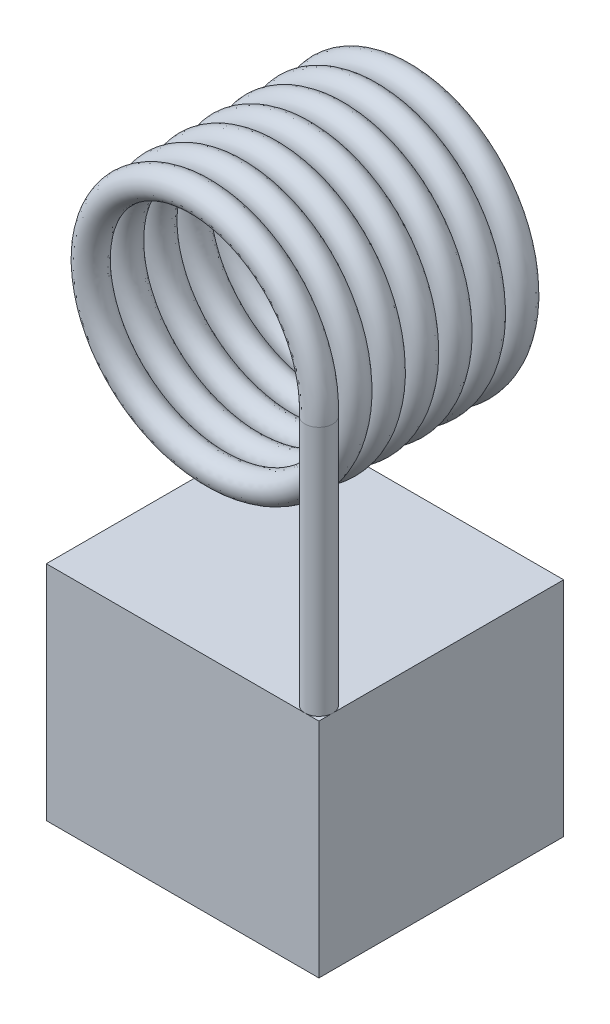
SolidWorks part; units mm, degrees
ref_plane "Front Plane" through (0, 0, 0) normal (0, 0, 1) x (1, 0, 0)
ref_plane "Top Plane" through (0, 0, 0) normal (0, 1, 0) x (1, 0, 0)
ref_plane "Right Plane" through (0, 0, 0) normal (1, 0, 0) x (0, 0, -1)
sketch "Sketch1" plane through (0, 0, 0) normal (0, 0, 1) x (1, 0, 0)
  line L5 (38.5919, -38.5919) -> (-39.5131, 39.5131) construction
  line L6 (38.5864, 38.5864) -> (-38.5864, -38.5864) construction
  circle A0 centre (0, 0) radius 55.88
  point P0 (0, 0)
  dimension "D3" = 111.76
curve "Helix/Spiral1" pitch 15.24 height 99.06 turns 6.5
sketch "Sketch2" plane through (0, 0, 0) normal (0, 1, 0) x (1, 0, 0)
  circle A0 centre (-55.88, 0) radius 6.35
  spline S0 degree 3 poles (-55.88, 0) (-55.88, -0.1534) (-55.2059, -0.4609) (-52.2086, -0.9215) (-47.3331, -1.3822) (-40.7549, -1.843) (-32.7104, -2.3037) (-23.4892, -2.7645) (-13.4229, -3.2252) (-2.8738, -3.686) (7.7787, -4.1467) (18.1514, -4.6074) (27.8711, -5.0682) (36.5881, -5.5289) (43.9888, -5.9897) (49.8071, -6.4504) (53.8335, -6.9112) (55.9233, -7.3719) (56.0012, -7.8327) (54.0644, -8.2934) (50.1827, -8.7541) (44.4956, -9.2149) (37.2078, -9.6756) (28.5815, -10.1364) (18.9269, -10.5971) (8.5914, -11.0579) (-2.0532, -11.5186) (-12.6239, -11.9793) (-22.7404, -12.4401) (-32.0389, -12.9008) (-40.1847, -13.3616) (-46.8849, -13.8223) (-51.8984, -14.2831) (-55.0449, -14.7438) (-56.2111, -15.2046) (-55.3551, -15.6653) (-52.5076, -16.126) (-47.7713, -16.5868) (-41.3163, -17.0475) (-33.375, -17.5083) (-24.233, -17.969) (-14.2192, -18.4298) (-3.6938, -18.8905) (6.9644, -19.3513) (17.372, -19.812) (27.1547, -20.2727) (35.9605, -20.7335) (43.4727, -21.1942) (49.4208, -21.655) (53.5911, -22.1157) (55.8334, -22.5765) (56.0671, -23.0372) (54.2838, -23.498) (50.5476, -23.9587) (44.9929, -24.4194) (37.8196, -24.8802) (29.2857, -25.3409) (19.6983, -25.8017) (9.4022, -26.2624) (-1.2321, -26.7232) (-11.8221, -27.1839) (-21.9868, -27.6447) (-31.3605, -28.1054) (-39.606, -28.5661) (-46.4267, -29.0269) (-51.5772, -29.4876) (-54.8721, -29.9484) (-56.1931, -30.4091) (-55.4924, -30.8699) (-52.7955, -31.3306) (-48.1992, -31.7913) (-41.8689, -32.2521) (-34.0324, -32.7128) (-24.9716, -33.1736) (-15.0124, -33.6343) (-4.5131, -34.0951) (6.1485, -34.5558) (16.589, -35.0166) (26.4326, -35.4773) (35.3253, -35.938) (42.9472, -36.3988) (49.0241, -36.8595) (53.3373, -37.3203) (55.7316, -37.781) (56.1211, -38.2418) (54.4915, -38.7025) (50.9016, -39.1633) (45.4806, -39.624) (38.4233, -40.0847) (29.9838, -40.5455) (20.4656, -41.0062) (10.2111, -41.467) (-0.4107, -41.9277) (-11.0178, -42.3885) (-21.2284, -42.8492) (-30.6754, -43.31) (-39.0188, -43.7707) (-45.9585, -44.2314) (-51.2449, -44.6922) (-54.6877, -45.1529) (-56.1631, -45.6137) (-55.618, -46.0744) (-53.072, -46.5352) (-48.6168, -46.9959) (-42.4126, -47.4567) (-34.6826, -47.9174) (-25.7048, -48.3781) (-15.8023, -48.8389) (-5.3314, -49.2996) (5.3314, -49.7604) (15.8023, -50.2211) (25.7048, -50.6819) (34.6826, -51.1426) (42.4126, -51.6033) (48.6168, -52.0641) (53.072, -52.5248) (55.618, -52.9856) (56.1631, -53.4463) (54.6877, -53.9071) (51.2449, -54.3678) (45.9585, -54.8286) (39.0188, -55.2893) (30.6754, -55.75) (21.2284, -56.2108) (11.0178, -56.6715) (0.4107, -57.1323) (-10.2111, -57.593) (-20.4656, -58.0538) (-29.9838, -58.5145) (-38.4233, -58.9753) (-45.4806, -59.436) (-50.9016, -59.8967) (-54.4915, -60.3575) (-56.1211, -60.8182) (-55.7316, -61.279) (-53.3373, -61.7397) (-49.0241, -62.2005) (-42.9472, -62.6612) (-35.3253, -63.122) (-26.4326, -63.5827) (-16.589, -64.0434) (-6.1485, -64.5042) (4.5131, -64.9649) (15.0124, -65.4257) (24.9716, -65.8864) (34.0324, -66.3472) (41.8689, -66.8079) (48.1992, -67.2687) (52.7955, -67.7294) (55.4924, -68.1901) (56.1931, -68.6509) (54.8721, -69.1116) (51.5772, -69.5724) (46.4267, -70.0331) (39.606, -70.4939) (31.3605, -70.9546) (21.9868, -71.4153) (11.8221, -71.8761) (1.2321, -72.3368) (-9.4022, -72.7976) (-19.6983, -73.2583) (-29.2857, -73.7191) (-37.8196, -74.1798) (-44.9929, -74.6406) (-50.5476, -75.1013) (-54.2838, -75.562) (-56.0671, -76.0228) (-55.8334, -76.4835) (-53.5911, -76.9443) (-49.4208, -77.405) (-43.4727, -77.8658) (-35.9605, -78.3265) (-27.1547, -78.7873) (-17.372, -79.248) (-6.9644, -79.7087) (3.6938, -80.1695) (14.2192, -80.6302) (24.233, -81.091) (33.375, -81.5517) (41.3163, -82.0125) (47.7713, -82.4732) (52.5076, -82.934) (55.3551, -83.3947) (56.2111, -83.8554) (55.0449, -84.3162) (51.8984, -84.7769) (46.8849, -85.2377) (40.1847, -85.6984) (32.0389, -86.1592) (22.7404, -86.6199) (12.6239, -87.0807) (2.0532, -87.5414) (-8.5914, -88.0021) (-18.9269, -88.4629) (-28.5815, -88.9236) (-37.2078, -89.3844) (-44.4956, -89.8451) (-50.1827, -90.3059) (-54.0644, -90.7666) (-56.0012, -91.2273) (-55.9233, -91.6881) (-53.8335, -92.1488) (-49.8071, -92.6096) (-43.9888, -93.0703) (-36.5881, -93.5311) (-27.8711, -93.9918) (-18.1514, -94.4526) (-7.7787, -94.9133) (2.8738, -95.374) (13.4229, -95.8348) (23.4892, -96.2955) (32.7104, -96.7563) (40.7549, -97.217) (47.3331, -97.6778) (52.2086, -98.1385) (55.2059, -98.5991) (55.88, -98.9066) (55.88, -99.06) knots 0 0 0 0 0.004651 0.009302 0.013953 0.018605 0.023256 0.027907 0.032558 0.037209 0.04186 0.046512 0.051163 0.055814 0.060465 0.065116 0.069767 0.074419 0.07907 0.083721 0.088372 0.093023 0.097674 0.102326 0.106977 0.111628 0.116279 0.12093 0.125581 0.130233 0.134884 0.139535 0.144186 0.148837 0.153488 0.15814 0.162791 0.167442 0.172093 0.176744 0.181395 0.186047 0.190698 0.195349 0.2 0.204651 0.209302 0.213953 0.218605 0.223256 0.227907 0.232558 0.237209 0.24186 0.246512 0.251163 0.255814 0.260465 0.265116 0.269767 0.274419 0.27907 0.283721 0.288372 0.293023 0.297674 0.302326 0.306977 0.311628 0.316279 0.32093 0.325581 0.330233 0.334884 0.339535 0.344186 0.348837 0.353488 0.35814 0.362791 0.367442 0.372093 0.376744 0.381395 0.386047 0.390698 0.395349 0.4 0.404651 0.409302 0.413953 0.418605 0.423256 0.427907 0.432558 0.437209 0.44186 0.446512 0.451163 0.455814 0.460465 0.465116 0.469767 0.474419 0.47907 0.483721 0.488372 0.493023 0.497674 0.502326 0.506977 0.511628 0.516279 0.52093 0.525581 0.530233 0.534884 0.539535 0.544186 0.548837 0.553488 0.55814 0.562791 0.567442 0.572093 0.576744 0.581395 0.586047 0.590698 0.595349 0.6 0.604651 0.609302 0.613953 0.618605 0.623256 0.627907 0.632558 0.637209 0.64186 0.646512 0.651163 0.655814 0.660465 0.665116 0.669767 0.674419 0.67907 0.683721 0.688372 0.693023 0.697674 0.702326 0.706977 0.711628 0.716279 0.72093 0.725581 0.730233 0.734884 0.739535 0.744186 0.748837 0.753488 0.75814 0.762791 0.767442 0.772093 0.776744 0.781395 0.786047 0.790698 0.795349 0.8 0.804651 0.809302 0.813953 0.818605 0.823256 0.827907 0.832558 0.837209 0.84186 0.846512 0.851163 0.855814 0.860465 0.865116 0.869767 0.874419 0.87907 0.883721 0.888372 0.893023 0.897674 0.902326 0.906977 0.911628 0.916279 0.92093 0.925581 0.930233 0.934884 0.939535 0.944186 0.948837 0.953488 0.95814 0.962791 0.967442 0.972093 0.976744 0.981395 0.986047 0.990698 0.995349 1 1 1 1 construction
  dimension "D1" = 12.7
sweep "Sweep1" add profiles "Sketch2" path "Helix/Spiral1"
sketch "Sketch3" plane through (0, 0, 0) normal (0, -1, 0) x (1, 0, 0)
  circle A0 centre (55.88, 99.06) radius 6.35
  circle A1 centre (-55.88, 0) radius 6.35
  spline S0 degree 3 poles (-55.88, 0) (-55.88, 0.1534) (-55.2059, 0.4609) (-52.2086, 0.9215) (-47.3331, 1.3822) (-40.7549, 1.843) (-32.7104, 2.3037) (-23.4892, 2.7645) (-13.4229, 3.2252) (-2.8738, 3.686) (7.7787, 4.1467) (18.1514, 4.6074) (27.8711, 5.0682) (36.5881, 5.5289) (43.9888, 5.9897) (49.8071, 6.4504) (53.8335, 6.9112) (55.9233, 7.3719) (56.0012, 7.8327) (54.0644, 8.2934) (50.1827, 8.7541) (44.4956, 9.2149) (37.2078, 9.6756) (28.5815, 10.1364) (18.9269, 10.5971) (8.5914, 11.0579) (-2.0532, 11.5186) (-12.6239, 11.9793) (-22.7404, 12.4401) (-32.0389, 12.9008) (-40.1847, 13.3616) (-46.8849, 13.8223) (-51.8984, 14.2831) (-55.0449, 14.7438) (-56.2111, 15.2046) (-55.3551, 15.6653) (-52.5076, 16.126) (-47.7713, 16.5868) (-41.3163, 17.0475) (-33.375, 17.5083) (-24.233, 17.969) (-14.2192, 18.4298) (-3.6938, 18.8905) (6.9644, 19.3513) (17.372, 19.812) (27.1547, 20.2727) (35.9605, 20.7335) (43.4727, 21.1942) (49.4208, 21.655) (53.5911, 22.1157) (55.8334, 22.5765) (56.0671, 23.0372) (54.2838, 23.498) (50.5476, 23.9587) (44.9929, 24.4194) (37.8196, 24.8802) (29.2857, 25.3409) (19.6983, 25.8017) (9.4022, 26.2624) (-1.2321, 26.7232) (-11.8221, 27.1839) (-21.9868, 27.6447) (-31.3605, 28.1054) (-39.606, 28.5661) (-46.4267, 29.0269) (-51.5772, 29.4876) (-54.8721, 29.9484) (-56.1931, 30.4091) (-55.4924, 30.8699) (-52.7955, 31.3306) (-48.1992, 31.7913) (-41.8689, 32.2521) (-34.0324, 32.7128) (-24.9716, 33.1736) (-15.0124, 33.6343) (-4.5131, 34.0951) (6.1485, 34.5558) (16.589, 35.0166) (26.4326, 35.4773) (35.3253, 35.938) (42.9472, 36.3988) (49.0241, 36.8595) (53.3373, 37.3203) (55.7316, 37.781) (56.1211, 38.2418) (54.4915, 38.7025) (50.9016, 39.1633) (45.4806, 39.624) (38.4233, 40.0847) (29.9838, 40.5455) (20.4656, 41.0062) (10.2111, 41.467) (-0.4107, 41.9277) (-11.0178, 42.3885) (-21.2284, 42.8492) (-30.6754, 43.31) (-39.0188, 43.7707) (-45.9585, 44.2314) (-51.2449, 44.6922) (-54.6877, 45.1529) (-56.1631, 45.6137) (-55.618, 46.0744) (-53.072, 46.5352) (-48.6168, 46.9959) (-42.4126, 47.4567) (-34.6826, 47.9174) (-25.7048, 48.3781) (-15.8023, 48.8389) (-5.3314, 49.2996) (5.3314, 49.7604) (15.8023, 50.2211) (25.7048, 50.6819) (34.6826, 51.1426) (42.4126, 51.6033) (48.6168, 52.0641) (53.072, 52.5248) (55.618, 52.9856) (56.1631, 53.4463) (54.6877, 53.9071) (51.2449, 54.3678) (45.9585, 54.8286) (39.0188, 55.2893) (30.6754, 55.75) (21.2284, 56.2108) (11.0178, 56.6715) (0.4107, 57.1323) (-10.2111, 57.593) (-20.4656, 58.0538) (-29.9838, 58.5145) (-38.4233, 58.9753) (-45.4806, 59.436) (-50.9016, 59.8967) (-54.4915, 60.3575) (-56.1211, 60.8182) (-55.7316, 61.279) (-53.3373, 61.7397) (-49.0241, 62.2005) (-42.9472, 62.6612) (-35.3253, 63.122) (-26.4326, 63.5827) (-16.589, 64.0434) (-6.1485, 64.5042) (4.5131, 64.9649) (15.0124, 65.4257) (24.9716, 65.8864) (34.0324, 66.3472) (41.8689, 66.8079) (48.1992, 67.2687) (52.7955, 67.7294) (55.4924, 68.1901) (56.1931, 68.6509) (54.8721, 69.1116) (51.5772, 69.5724) (46.4267, 70.0331) (39.606, 70.4939) (31.3605, 70.9546) (21.9868, 71.4153) (11.8221, 71.8761) (1.2321, 72.3368) (-9.4022, 72.7976) (-19.6983, 73.2583) (-29.2857, 73.7191) (-37.8196, 74.1798) (-44.9929, 74.6406) (-50.5476, 75.1013) (-54.2838, 75.562) (-56.0671, 76.0228) (-55.8334, 76.4835) (-53.5911, 76.9443) (-49.4208, 77.405) (-43.4727, 77.8658) (-35.9605, 78.3265) (-27.1547, 78.7873) (-17.372, 79.248) (-6.9644, 79.7087) (3.6938, 80.1695) (14.2192, 80.6302) (24.233, 81.091) (33.375, 81.5517) (41.3163, 82.0125) (47.7713, 82.4732) (52.5076, 82.934) (55.3551, 83.3947) (56.2111, 83.8554) (55.0449, 84.3162) (51.8984, 84.7769) (46.8849, 85.2377) (40.1847, 85.6984) (32.0389, 86.1592) (22.7404, 86.6199) (12.6239, 87.0807) (2.0532, 87.5414) (-8.5914, 88.0021) (-18.9269, 88.4629) (-28.5815, 88.9236) (-37.2078, 89.3844) (-44.4956, 89.8451) (-50.1827, 90.3059) (-54.0644, 90.7666) (-56.0012, 91.2273) (-55.9233, 91.6881) (-53.8335, 92.1488) (-49.8071, 92.6096) (-43.9888, 93.0703) (-36.5881, 93.5311) (-27.8711, 93.9918) (-18.1514, 94.4526) (-7.7787, 94.9133) (2.8738, 95.374) (13.4229, 95.8348) (23.4892, 96.2955) (32.7104, 96.7563) (40.7549, 97.217) (47.3331, 97.6778) (52.2086, 98.1385) (55.2059, 98.5991) (55.88, 98.9066) (55.88, 99.06) knots 0 0 0 0 0.004651 0.009302 0.013953 0.018605 0.023256 0.027907 0.032558 0.037209 0.04186 0.046512 0.051163 0.055814 0.060465 0.065116 0.069767 0.074419 0.07907 0.083721 0.088372 0.093023 0.097674 0.102326 0.106977 0.111628 0.116279 0.12093 0.125581 0.130233 0.134884 0.139535 0.144186 0.148837 0.153488 0.15814 0.162791 0.167442 0.172093 0.176744 0.181395 0.186047 0.190698 0.195349 0.2 0.204651 0.209302 0.213953 0.218605 0.223256 0.227907 0.232558 0.237209 0.24186 0.246512 0.251163 0.255814 0.260465 0.265116 0.269767 0.274419 0.27907 0.283721 0.288372 0.293023 0.297674 0.302326 0.306977 0.311628 0.316279 0.32093 0.325581 0.330233 0.334884 0.339535 0.344186 0.348837 0.353488 0.35814 0.362791 0.367442 0.372093 0.376744 0.381395 0.386047 0.390698 0.395349 0.4 0.404651 0.409302 0.413953 0.418605 0.423256 0.427907 0.432558 0.437209 0.44186 0.446512 0.451163 0.455814 0.460465 0.465116 0.469767 0.474419 0.47907 0.483721 0.488372 0.493023 0.497674 0.502326 0.506977 0.511628 0.516279 0.52093 0.525581 0.530233 0.534884 0.539535 0.544186 0.548837 0.553488 0.55814 0.562791 0.567442 0.572093 0.576744 0.581395 0.586047 0.590698 0.595349 0.6 0.604651 0.609302 0.613953 0.618605 0.623256 0.627907 0.632558 0.637209 0.64186 0.646512 0.651163 0.655814 0.660465 0.665116 0.669767 0.674419 0.67907 0.683721 0.688372 0.693023 0.697674 0.702326 0.706977 0.711628 0.716279 0.72093 0.725581 0.730233 0.734884 0.739535 0.744186 0.748837 0.753488 0.75814 0.762791 0.767442 0.772093 0.776744 0.781395 0.786047 0.790698 0.795349 0.8 0.804651 0.809302 0.813953 0.818605 0.823256 0.827907 0.832558 0.837209 0.84186 0.846512 0.851163 0.855814 0.860465 0.865116 0.869767 0.874419 0.87907 0.883721 0.888372 0.893023 0.897674 0.902326 0.906977 0.911628 0.916279 0.92093 0.925581 0.930233 0.934884 0.939535 0.944186 0.948837 0.953488 0.95814 0.962791 0.967442 0.972093 0.976744 0.981395 0.986047 0.990698 0.995349 1 1 1 1 construction
extrude "Boss-Extrude1" add sketch "Sketch3" along normal blind 152.4
sketch "Sketch4" plane through (0, -152.4, 0) normal (0, -1, 0) x (1, 0, 0)
  line L1 (62.23, 105.41) -> (-62.23, 105.41)
  line L2 (62.23, 105.41) -> (62.23, -6.35)
  line L3 (62.23, -6.35) -> (-62.23, -6.35)
  line L4 (-62.23, 105.41) -> (-62.23, -6.35)
  circle A0 centre (-55.88, 0) radius 6.35 construction
  circle A1 centre (55.88, 99.06) radius 6.35 construction
extrude "Boss-Extrude2" add sketch "Sketch4" along normal blind 63.5 and the other way blind 38.1
